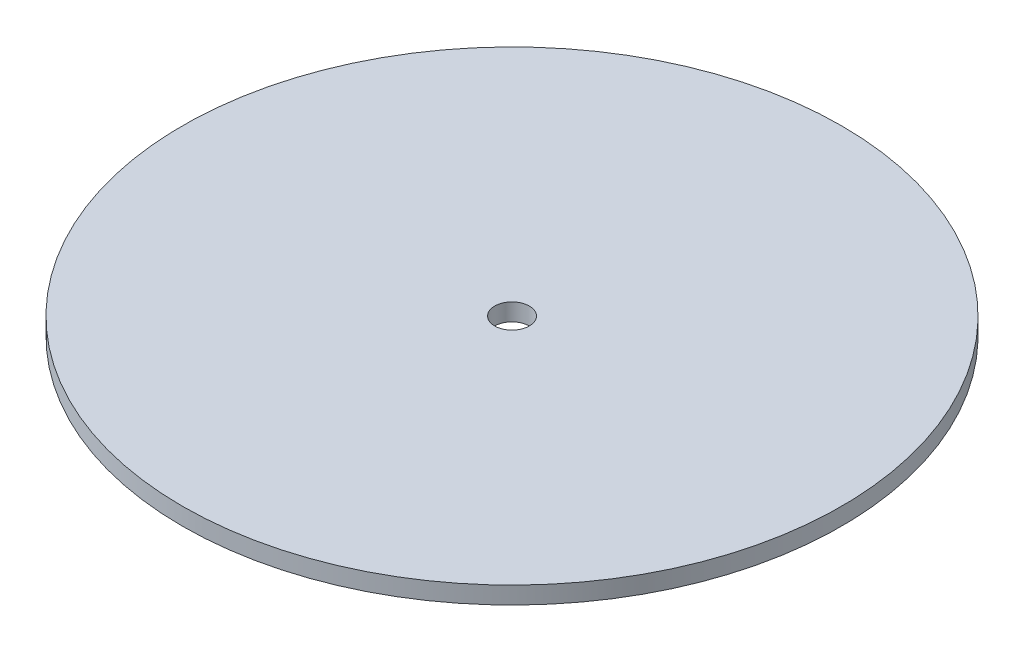
SolidWorks part; units mm, degrees
ref_plane "Front Plane" through (0, 0, 0) normal (0, 0, 1) x (1, 0, 0)
ref_plane "Top Plane" through (0, 0, 0) normal (0, 1, 0) x (1, 0, 0)
ref_plane "Right Plane" through (0, 0, 0) normal (1, 0, 0) x (0, 0, -1)
sketch "Sketch1" plane through (0, 0, 0) normal (0, 1, 0) x (1, 0, 0)
  circle A0 centre (0, 0) radius 76.2
  circle A1 centre (0, 0) radius 4
  dimension "D1" = 152.4
  dimension "D2" = 8
extrude "Boss-Extrude1" add sketch "Sketch1" along normal blind 4 contours A0 A1
